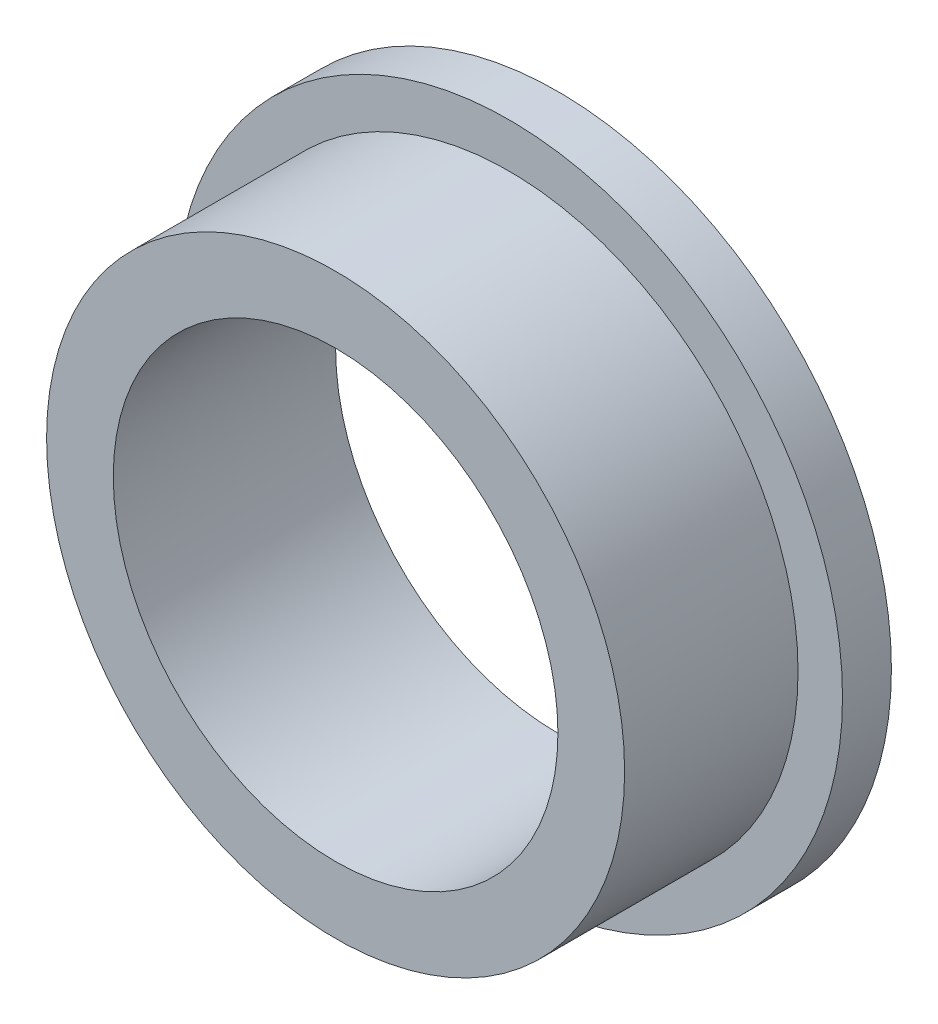
SolidWorks part; units mm, degrees
ref_plane "前视基准面" through (0, 0, 0) normal (0, 0, 1) x (1, 0, 0)
ref_plane "上视基准面" through (0, 0, 0) normal (0, 1, 0) x (1, 0, 0)
ref_plane "右视基准面" through (0, 0, 0) normal (1, 0, 0) x (0, 0, -1)
sketch "草图1" plane through (0, 0, 0) normal (0, 0, 1) x (1, 0, 0)
  circle A0 centre (0, 0) radius 5
  circle A1 centre (0, 0) radius 6.5
extrude "凸台-拉伸1" add sketch "草图1" along normal blind 5
sketch "草图2" plane through (0, 0, 0) normal (0, 0, 1) x (1, 0, 0)
  circle A0 centre (0, 0) radius 6.5
  circle A1 centre (0, 0) radius 7.5
extrude "凸台-拉伸2" add sketch "草图2" along normal blind 1.1
